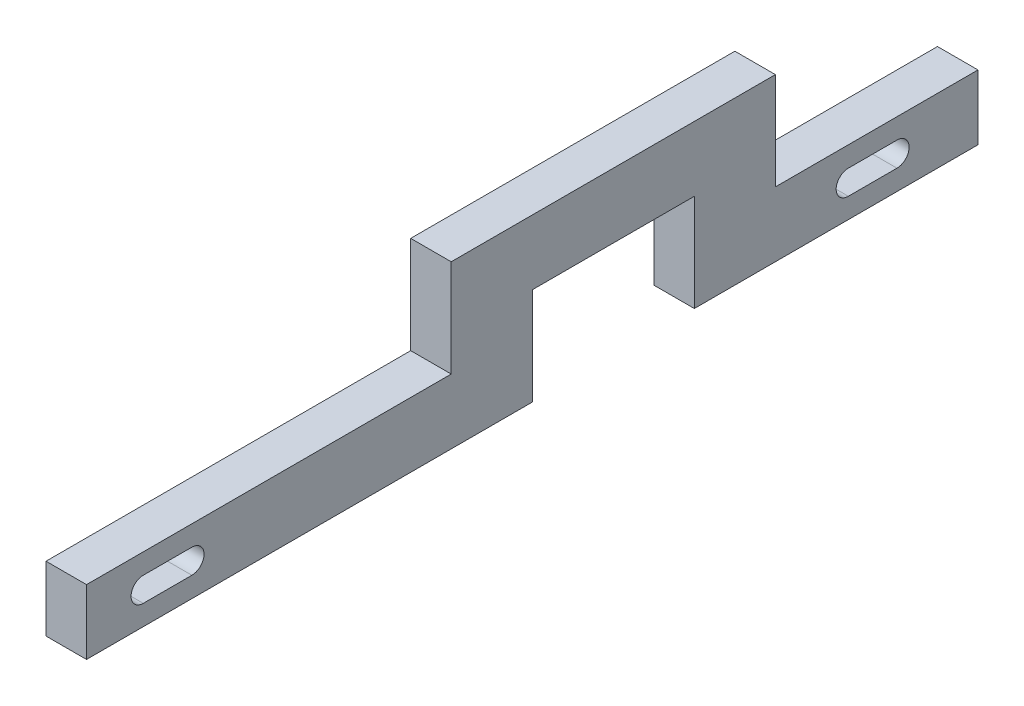
SolidWorks part; units mm, degrees
ref_plane "前视基准面" through (0, 0, 0) normal (0, 0, 1) x (1, 0, 0)
ref_plane "上视基准面" through (0, 0, 0) normal (0, 1, 0) x (1, 0, 0)
ref_plane "右视基准面" through (0, 0, 0) normal (1, 0, 0) x (0, 0, -1)
sketch "草图1" plane through (0, 0, 0) normal (1, 0, 0) x (0, 0, -1)
  line L0 (44.5923, 21.6133) -> (44.5923, -15.1602) construction
  line L1 (-30.4077, 7.8124) -> (14.5923, 7.8124)
  line L2 (-30.4077, 7.8124) -> (-30.4077, -0.1876)
  line L3 (-30.4077, -0.1876) -> (24.5923, -0.1876)
  line L4 (79.5923, 7.8124) -> (79.5923, -0.1876)
  line L5 (24.5923, 23.7348) -> (24.5923, -13.0387) construction
  line L6 (44.5923, 7.8124) -> (44.5923, 11.8124)
  line L7 (44.5923, 11.8124) -> (24.5923, 11.8124)
  line L8 (24.5923, 11.8124) -> (24.5923, 3.8124)
  line L9 (24.5923, 3.8124) -> (24.5923, -0.1876)
  line L10 (44.5923, 7.8124) -> (44.5923, -0.1876)
  line L11 (54.5923, 7.8124) -> (54.5923, 19.8124)
  line L12 (54.5923, 19.8124) -> (14.5923, 19.8124)
  line L13 (14.5923, 7.8124) -> (14.5923, 19.8124)
  line L14 (54.5923, 7.8124) -> (79.5923, 7.8124)
  line L15 (44.5923, -0.1876) -> (79.5923, -0.1876)
  line L16 (-23.4077, 3.8124) -> (-17.4077, 3.8124) construction
  line L17 (-23.4077, 5.3124) -> (-17.4077, 5.3124)
  line L18 (-23.4077, 2.3124) -> (-17.4077, 2.3124)
  line L19 (69.5923, 3.8124) -> (63.5923, 3.8124) construction
  line L20 (69.5923, 2.3124) -> (63.5923, 2.3124)
  line L21 (69.5923, 5.3124) -> (63.5923, 5.3124)
  arc A0 (-23.4077, 5.3124) -> (-23.4077, 2.3124) centre (-23.4077, 3.8124) ccw
  arc A1 (-17.4077, 2.3124) -> (-17.4077, 5.3124) centre (-17.4077, 3.8124) ccw
  arc A2 (69.5923, 2.3124) -> (69.5923, 5.3124) centre (69.5923, 3.8124) ccw
  arc A3 (63.5923, 5.3124) -> (63.5923, 2.3124) centre (63.5923, 3.8124) ccw
  point P20 (-20.4077, 3.8124)
  point P25 (66.5923, 3.8124)
  point P32 (-15.876, 3.8124)
  dimension "D5" = 40
  dimension "D1" = 8
  dimension "D2" = 110
  dimension "D3" = 35
  dimension "D4" = 20
  dimension "D6" = 10
  dimension "D7" = 6
  dimension "D8" = 6
  dimension "D9" = 10
  dimension "D10" = 4
  dimension "D11" = 12
  dimension "D12" = 12
  dimension "D13" = 7
extrude "凸台-拉伸1" add sketch "草图1" along normal blind 5
